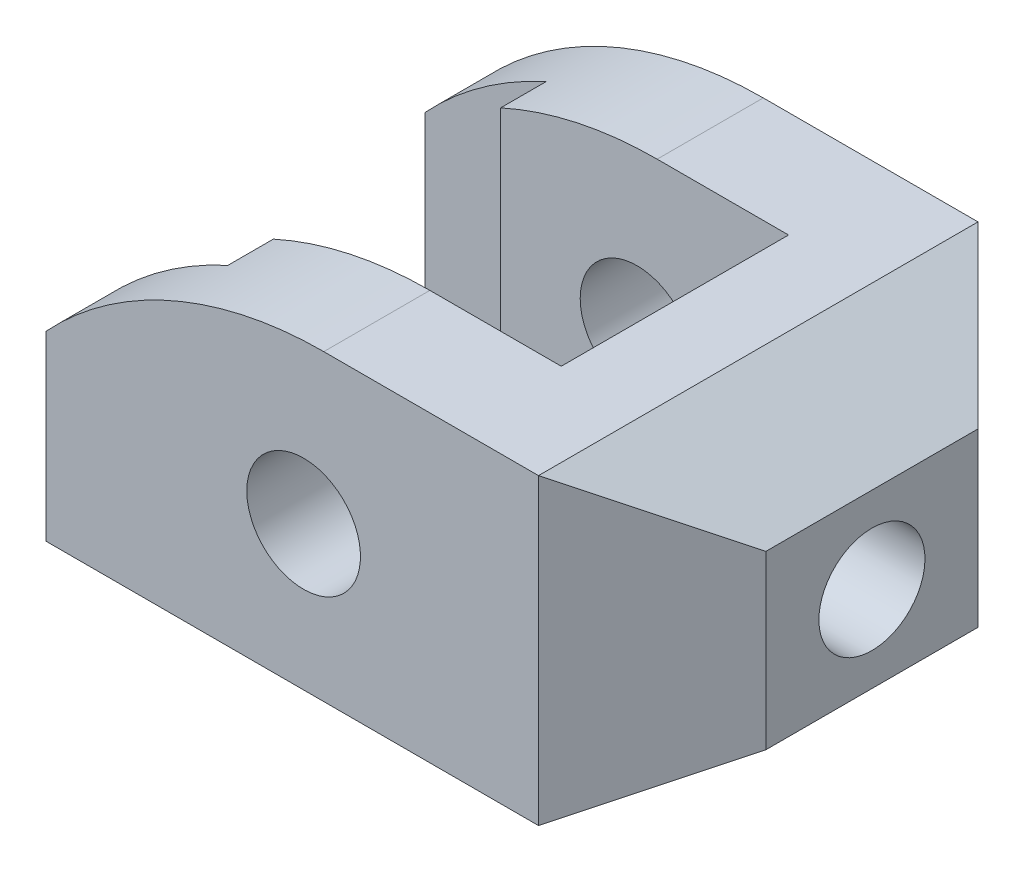
SolidWorks part; units mm, degrees
material "1060 Alloy"
ref_plane "Front Plane" through (0, 0, 0) normal (0, 0, 1) x (1, 0, 0)
ref_plane "Top Plane" through (0, 0, 0) normal (0, 1, 0) x (1, 0, 0)
ref_plane "Right Plane" through (0, 0, 0) normal (1, 0, 0) x (0, 0, -1)
sketch "Sketch1" plane through (0, 0, 0) normal (0, 0, 1) x (1, 0, 0)
  line L0 (0, -20.9292) -> (0, 20.9292) construction
  line L1 (-46, 0) -> (46, 0) construction
  line L2 (-34, 5) -> (-34, -19)
  line L3 (-34, -19) -> (31, -19)
  line L4 (31, -19) -> (46, -10.3397)
  line L5 (46, -10.3397) -> (46, 12.3397)
  line L6 (46, 12.3397) -> (31, 21)
  line L7 (31, 21) -> (2.6606, 21)
  circle A0 centre (0, 0) radius 7.5
  arc A1 (-34, 5) -> (2.6606, 21) centre (2.6606, -29) cw
  point P4 (0, 0)
  point P8 (0, 0)
  dimension "D1" = 15
  dimension "D10" = 50
  dimension "D2" = 24
  dimension "D3" = 65
  dimension "D4" = 40
  dimension "D5" = 19
  dimension "D6" = 31
  dimension "D7" = 15
  dimension "D8" = 30
  dimension "D9" = 30
  dimension "D11" = 21
extrude "Boss-Extrude1" add sketch "Sketch1" along normal blind 58
sketch "Sketch3" plane through (0, -19, 0) normal (0, -1, 0) x (1, 0, 0)
  line L0 (-47.2082, 29) -> (47.2082, 29) construction
  line L1 (-34, 58) -> (31, 58) construction
  line L2 (-34, 58) -> (-34, 50)
  line L3 (-34, 58) -> (-34, 0) construction
  line L4 (-34, 50) -> (-18, 50)
  line L5 (-18, 50) -> (-18, 44)
  line L6 (-18, 44) -> (20, 44)
  line L7 (20, 44) -> (20, 14)
  line L8 (20, 14) -> (-18, 14)
  line L9 (-18, 14) -> (-18, 8)
  line L10 (-18, 8) -> (-34, 8)
  line L11 (-34, 8) -> (-34, 0)
  line L12 (-34, 50) -> (-34, 8)
  point P3 (0, 29)
  line M14 (-34, 58) -> (-34, 0)
  dimension "D1" = 29
  dimension "D2" = 8
  dimension "D3" = 6
  dimension "D4" = 16
  dimension "D5" = 11
  dimension "D6" = 8
  dimension "D7" = 16
  dimension "D8" = 6
extrude "Cut-Extrude1" cut sketch "Sketch3" against normal blind 58 contours L0 L7 L6 L5 L4 M14 | L0 L12 L10 L9 L8 L7
sketch "Sketch4" plane through (0, 0, 0) normal (0, 1, 0) x (1, 0, 0)
  line L0 (31, 0) -> (31, -58)
  line L1 (31, -58) -> (46, -43)
  line L2 (46, -58) -> (46, 0) construction
  line L3 (46, -43) -> (46, -15)
  line L4 (46, -15) -> (31, 0)
  line L5 (46, -58) -> (31, -58) construction
  line L6 (46, 0) -> (31, 0) construction
  line L7 (31, 0) -> (46, 0)
  line L8 (46, 0) -> (46, -15)
  line L9 (31, -58) -> (46, -58)
  line L10 (46, -58) -> (46, -43)
  dimension "D1" = 45
  dimension "D2" = 45
extrude "Cut-Extrude2" cut sketch "Sketch4" against normal blind 58 and the other way blind 58 contours L9 L10 L1 | L8 L7 L4
sketch "Sketch5" plane through (46, 0, 0) normal (1, 0, 0) x (0, 0, -1)
  line L0 (-29, 12.3397) -> (-29, -10.3397) construction
  line L1 (-43, 12.3397) -> (-15, 12.3397) construction
  line L2 (-43, -10.3397) -> (-15, -10.3397) construction
  line L3 (-43, 1) -> (-15, 1) construction
  line L4 (-43, 12.3397) -> (-43, -10.3397) construction
  line L5 (-15, 12.3397) -> (-15, -10.3397) construction
  circle A0 centre (-29, 1) radius 7
  dimension "D1" = 14
extrude "Cut-Extrude3" cut sketch "Sketch5" against normal blind 58
sketch "Sketch6" plane through (0, 0, 58) normal (0, 0, 1) x (1, 0, 0)
  line L0 (-34, -19) -> (31, -19) construction
  line L1 (2.6469, 19) -> (29, 19)
  line L2 (-18, 14.106) -> (-18, -17)
  line L3 (-18, -17) -> (29, -17)
  line L4 (29, 19) -> (29, -17)
  line L6 (31, 21) -> (2.6606, 21) construction
  line L7 (31, 21) -> (31, -19) construction
  line L8 (-34, 5) -> (-34, -19) construction
  line L9 (-32, 3.2588) -> (-32, -17)
  line L10 (-32, -17) -> (-18, -17)
  circle A0 centre (0, 0) radius 7.5
  arc A1 (2.6469, 19) -> (-32, 3.2588) centre (2.6469, -27) ccw
  arc A2 (2.6606, 21) -> (-34, 5) centre (2.6606, -29) ccw construction
  dimension "D5" = 2
  dimension "D7" = 46
  dimension "D8" = 15
  dimension "D1" = 2
  dimension "D2" = 2
  dimension "D3" = 2
  dimension "D4" = 16
  dimension "D6" = 2
